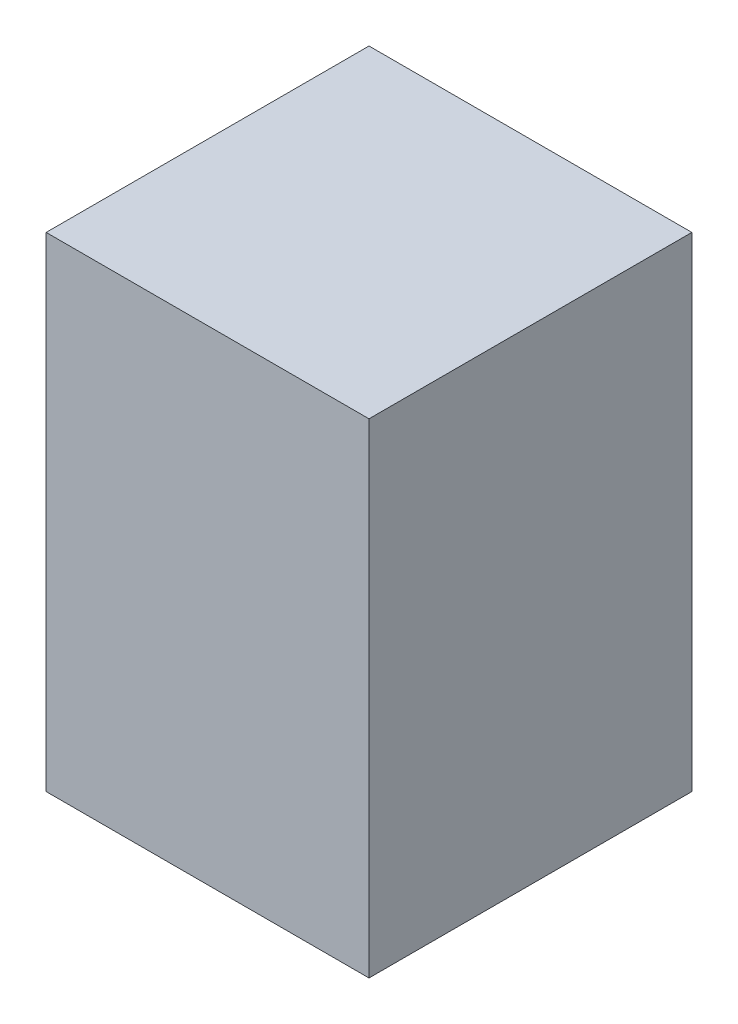
SolidWorks part; units mm, degrees
ref_plane "Front Plane" through (0, 0, 0) normal (0, 0, 1) x (1, 0, 0)
ref_plane "Top Plane" through (0, 0, 0) normal (0, 1, 0) x (1, 0, 0)
ref_plane "Right Plane" through (0, 0, 0) normal (1, 0, 0) x (0, 0, -1)
other "Configuration Table"
sketch "Sketch1" plane through (0, 0, 0) normal (0, 0, 1) x (1, 0, 0)
  line L1 (560, 0) -> (640, 0)
  line L2 (560, 0) -> (560, 120)
  line L3 (560, 120) -> (640, 120)
  line L4 (640, 0) -> (640, 120)
extrude "PRESS_ayak_2_1" add sketch "Sketch1" against normal blind 80 from offset 40 separate body
